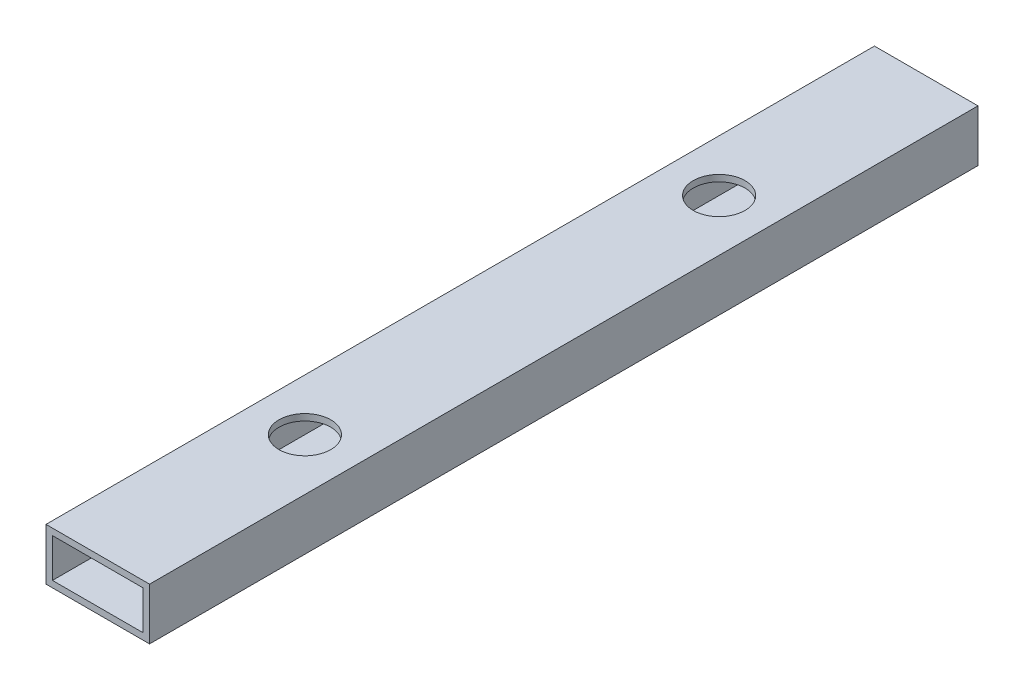
SolidWorks part; units mm, degrees
ref_plane "Front Plane" through (0, 0, 0) normal (0, 0, 1) x (1, 0, 0)
ref_plane "Top Plane" through (0, 0, 0) normal (0, 1, 0) x (1, 0, 0)
ref_plane "Right Plane" through (0, 0, 0) normal (1, 0, 0) x (0, 0, -1)
sketch "Sketch2" plane through (0, 0, 0) normal (0, 0, 1) x (1, 0, 0)
  line L1 (0, 0) -> (50.8, 0)
  line L2 (0, 0) -> (0, 25.4)
  line L3 (0, 25.4) -> (50.8, 25.4)
  line L4 (50.8, 0) -> (50.8, 25.4)
  line L5 (3.175, 22.225) -> (47.625, 22.225)
  line L6 (3.175, 22.225) -> (3.175, 3.175)
  line L7 (3.175, 3.175) -> (47.625, 3.175)
  line L8 (47.625, 22.225) -> (47.625, 3.175)
  dimension "D1" = 50.8
  dimension "D2" = 25.4
  dimension "D3" = 3.175
  dimension "D4" = 3.175
  dimension "D5" = 3.175
  dimension "D6" = 3.175
extrude "Boss-Extrude1" add sketch "Sketch2" along normal blind 406.4
sketch "Sketch3" plane through (0, 25.4, 0) normal (0, 1, 0) x (1, 0, 0)
  line L2 (50.8, 0) -> (0, 0) construction
  circle A0 centre (25.4, -101.6) radius 12.7
  circle A1 centre (25.4, -304.8) radius 12.7
  dimension "D1" = 25.4
  dimension "D2" = 25.4
  dimension "D3" = 203.2
  dimension "D4" = 101.6
extrude "Cut-Extrude1" cut sketch "Sketch3" against normal blind 12.7
